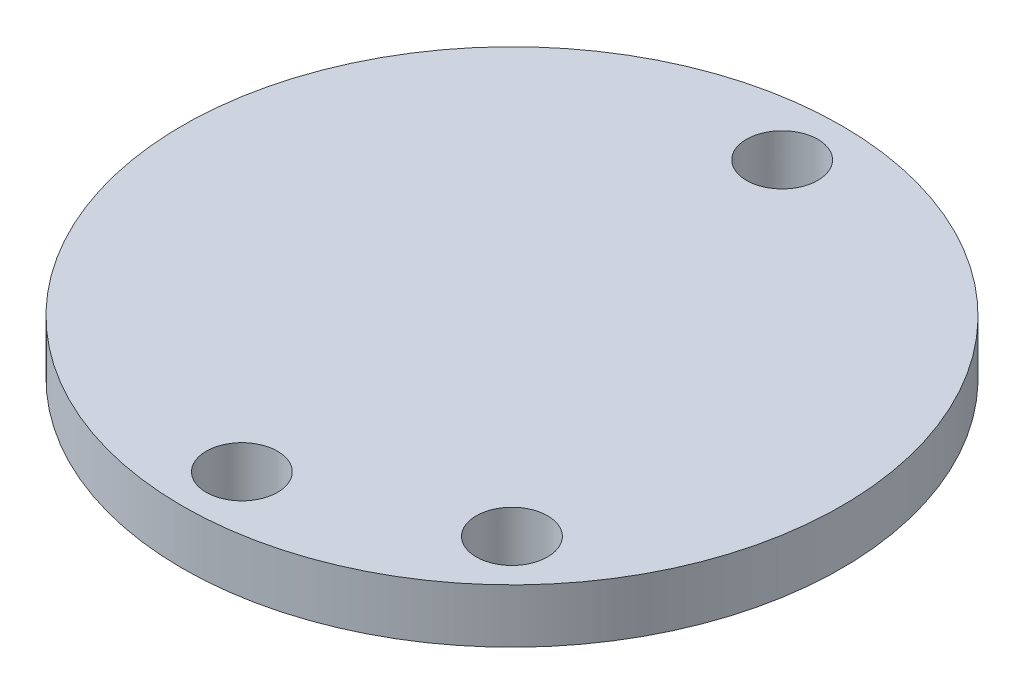
SolidWorks part; units mm, degrees
ref_plane "Front Plane" through (0, 0, 0) normal (0, 0, 1) x (1, 0, 0)
ref_plane "Top Plane" through (0, 0, 0) normal (0, 1, 0) x (1, 0, 0)
ref_plane "Right Plane" through (0, 0, 0) normal (1, 0, 0) x (0, 0, -1)
sketch "Sketch1" plane through (0, 0, 0) normal (0, 1, 0) x (1, 0, 0)
  circle A0 centre (0, 0) radius 30.5
extrude "Boss-Extrude1" add sketch "Sketch1" along normal blind 5
sketch "Sketch4" plane through (0, 0, 0) normal (0, -1, 0) x (-1, 0, 0)
  circle A0 centre (0, 25) radius 3.302
  point P0 (0, 25)
  dimension "D1" = 25
extrude "Cut-Extrude2" cut sketch "Sketch4" against normal blind 5.08
sketch "Sketch5" plane through (0, 0, 0) normal (0, -1, 0) x (1, 0, 0)
  circle A0 centre (0, 25) radius 3.302
  point P0 (0, 25)
  dimension "D1" = 25
extrude "Cut-Extrude3" cut sketch "Sketch5" against normal blind 5.08
sketch "Sketch6" plane through (0, 0, 0) normal (0, -1, 0) x (1, 0, 0)
  circle A0 centre (0, 25) radius 3.302 construction
  circle A1 centre (17.6745, 17.6809) radius 3.302
  point P0 (17.6745, 17.6809)
  dimension "D1" = 25
  dimension "D2" = 19.13
extrude "Cut-Extrude4" cut sketch "Sketch6" against normal blind 5.08
